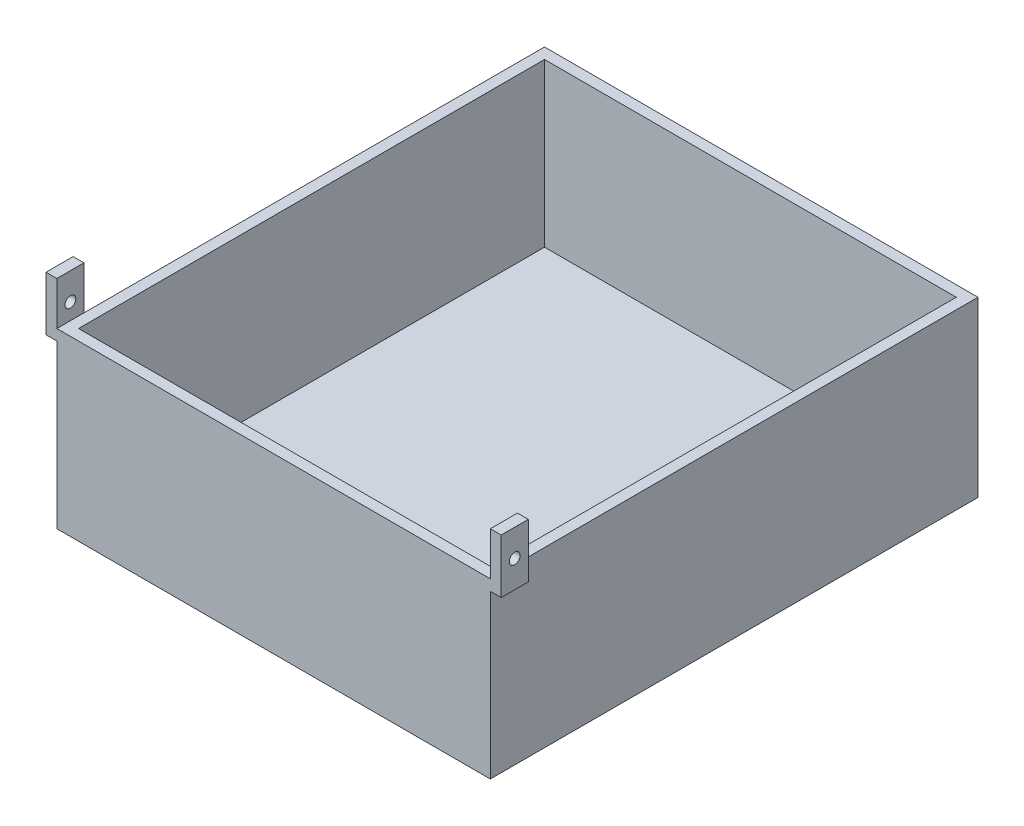
SolidWorks part; units mm, degrees
ref_plane "Front Plane" through (0, 0, 0) normal (0, 0, 1) x (1, 0, 0)
ref_plane "Top Plane" through (0, 0, 0) normal (0, 1, 0) x (1, 0, 0)
ref_plane "Right Plane" through (0, 0, 0) normal (1, 0, 0) x (0, 0, -1)
sketch "Sketch1" plane through (0, 0, 0) normal (0, 1, 0) x (1, 0, 0)
  line L1 (40, -45) -> (-40, -45)
  line L2 (40, -45) -> (40, 45)
  line L3 (40, 45) -> (-40, 45)
  line L4 (-40, -45) -> (-40, 45)
  line L5 (40, -45) -> (-40, 45) construction
  line L6 (40, 45) -> (-40, -45) construction
  point P0 (0, 0)
  dimension "D1" = 90
  dimension "D2" = 80
extrude "Boss-Extrude1" add sketch "Sketch1" along normal blind 2
sketch "Sketch2" plane through (0, 2, 0) normal (0, 1, 0) x (1, 0, 0)
  line L10 (40, 45) -> (-40, 45) construction
  line L11 (40, 45) -> (-40, 45)
  line L12 (-40, 45) -> (-40, -45) construction
  line L13 (-40, 45) -> (-40, -45)
  line L14 (38, -43) -> (38, 43)
  line L15 (-38, -43) -> (38, -43)
  line L16 (-38, 43) -> (-38, -43)
  line L17 (38, 43) -> (-38, 43)
  line L18 (38, -43) -> (38, 43)
  line L19 (-38, -43) -> (38, -43)
  line L20 (-38, 43) -> (-38, -43)
  line L21 (38, 43) -> (-38, 43)
  line L22 (40, -45) -> (40, 45) construction
  line L23 (40, -45) -> (40, 45)
  line L24 (-40, -45) -> (40, -45) construction
  line L25 (-40, -45) -> (40, -45)
  dimension "D1" = 2
extrude "Boss-Extrude2" add sketch "Sketch2" along normal blind 30
sketch "Sketch4" plane through (40, 0, 0) normal (1, 0, 0) x (0, 0, -1)
  line L0 (-45, 32) -> (-45, 0) construction
  line L1 (-45, 30) -> (-40, 30)
  line L2 (-45, 30) -> (-45, 40)
  line L3 (-45, 40) -> (-40, 40)
  line L4 (-40, 30) -> (-40, 40)
  line L5 (-42.5, 40) -> (-42.5, 30) construction
  circle A0 centre (-42.5, 35) radius 1
  dimension "D4" = 2
  dimension "D1" = 10
  dimension "D2" = 5
  dimension "D3" = 2
  dimension "D5" = 5
extrude "Boss-Extrude3" add sketch "Sketch4" along normal blind 2
sketch "Sketch5" plane through (-40, 0, 0) normal (-1, 0, 0) x (0, 0, 1)
  line L0 (45, 32) -> (45, 0) construction
  line L1 (45, 30) -> (40, 30)
  line L2 (45, 30) -> (45, 40)
  line L3 (45, 40) -> (40, 40)
  line L4 (40, 30) -> (40, 40)
  line L5 (42.5, 40) -> (42.5, 30) construction
  circle A0 centre (42.5, 35) radius 1
  dimension "D4" = 2
  dimension "D1" = 2
  dimension "D2" = 5
  dimension "D3" = 10
  dimension "D5" = 5
extrude "Boss-Extrude4" add sketch "Sketch5" along normal blind 2
